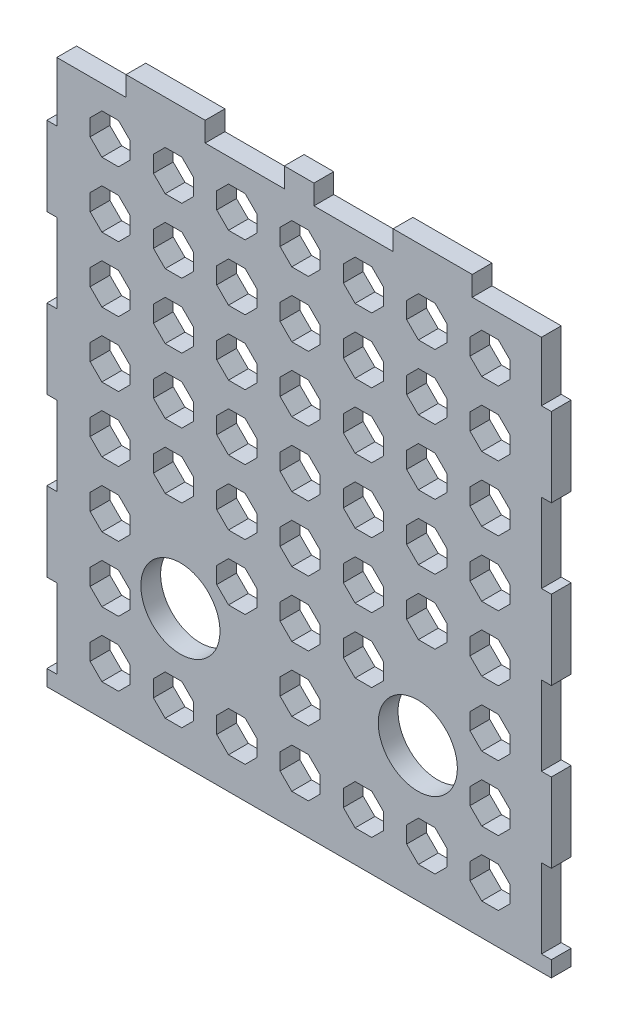
SolidWorks part; units mm, degrees
material "Oak"
ref_plane "Front Plane" through (0, 0, 0) normal (0, 0, 1) x (1, 0, 0)
ref_plane "Top Plane" through (0, 0, 0) normal (0, 1, 0) x (1, 0, 0)
ref_plane "Right Plane" through (0, 0, 0) normal (1, 0, 0) x (0, 0, -1)
sketch "Sketch1" plane through (0, 0, 0) normal (0, 0, 1) x (1, 0, 0)
  line L1 (0, 0) -> (80.9625, 0)
  line L2 (0, 0) -> (0, -91.44)
  line L3 (0, -91.44) -> (80.9625, -91.44)
  line L4 (80.9625, 0) -> (80.9625, -91.44)
extrude "Boss-Extrude1" add sketch "Sketch1" along normal blind 3.175
sketch "Sketch2" plane through (0, 0, 3.175) normal (0, 0, 1) x (1, 0, 0)
  line L0 (0, 0) -> (1.5875, 0)
  line L1 (80.9625, 0) -> (0, 0) construction
  line L2 (1.5875, 0) -> (1.5875, -12.7)
  line L3 (1.5875, -12.7) -> (0, -12.7)
  line L4 (0, 0) -> (0, -91.44) construction
  line L5 (0, -12.7) -> (0, 0)
extrude "Cut-Extrude1" cut sketch "Sketch2" against normal through all
pattern_linear "LPattern1" count 5 spacing 25.4 along (0, -1, 0) of "Cut-Extrude1"
sketch "Sketch5" plane through (0, 0, 3.175) normal (0, 0, 1) x (1, 0, 0)
  line L1 (0, 0) -> (12.7, 0)
  line L2 (0, 0) -> (0, -3.175)
  line L3 (0, -3.175) -> (12.7, -3.175)
  line L4 (12.7, 0) -> (12.7, -3.175)
extrude "Cut-Extrude2" cut sketch "Sketch5" against normal through all
pattern_linear "LPattern2" count 2 spacing 25.4 along (1, 0, 0) of "Cut-Extrude2"
ref_plane "Plane1" through (40.4812, 0, 0) normal (1, 0, 0) x (0, 0, -1)
hole_wizard "Hole1" positions "Sketch7" profile "Sketch6" legacy
sketch "Sketch7" plane through (0, 0, 3.175) normal (0, 0, 1) x (1, 0, 0)
  line L0 (40.4812, -1.7463) -> (40.4812, 1.7463) construction
  line L1 (25.4, 0) -> (12.7, 0) construction
  point P0 (21.4312, -69.85)
  point P11 (19.05, 0)
  dimension "D1" = 19.05
  dimension "D2" = 69.85
sketch "Sketch6" plane through (21.4312, -69.85, 3.175) normal (1, 0, 0) x (0, -1, 0)
  line L0 (0, 0) -> (0, 93.98)
  line L1 (0, 93.98) -> (6.35, 93.98)
  line L2 (6.35, 93.98) -> (6.35, 0)
  line L3 (6.35, 0) -> (0, 0)
  line L4 (0, 110) -> (0, -10) construction
  dimension "Diameter" = 12.7
  dimension "Depth" = 93.98
mirror "Mirror1" about plane through (40.4812, 0, 0) normal (1, 0, 0) of "Hole1", "Cut-Extrude1", "LPattern1", "Cut-Extrude2", "LPattern2"
hole_wizard "Hole2" [suppressed] positions "Sketch9" profile "Sketch8" legacy
sketch "Sketch9" plane through (0, 0, 2.54) normal (0, 0, 1) x (1, 0, 0)
  point P0 (10.16, -10.16)
sketch "Sketch8" plane through (10.16, -10.16, 2.54) normal (1, 0, 0) x (0, -1, 0)
  line L0 (0, 0) -> (0, 2.54)
  line L1 (0, 2.54) -> (3.175, 2.54)
  line L2 (3.175, 2.54) -> (3.175, 0)
  line L3 (3.175, 0) -> (0, 0)
  line L4 (0, 110) -> (0, -10) construction
  dimension "Diameter" = 6.35
  dimension "Depth" = 2.54
pattern_linear "LPattern5" [suppressed] count 8 spacing 10.16 count 7 spacing 10.1071
sketch "Sketch10" plane through (0, 0, 3.175) normal (0, 0, 1) x (1, 0, 0)
  line L1 (13.3794, -8.8709) -> (11.4935, -6.985)
  line L2 (11.4935, -6.985) -> (8.8265, -6.985)
  line L3 (8.8265, -6.985) -> (6.9406, -8.8709)
  line L4 (6.9406, -8.8709) -> (6.9406, -11.5379)
  line L5 (6.9406, -11.5379) -> (8.8265, -13.4237)
  line L6 (8.8265, -13.4237) -> (11.4935, -13.4237)
  line L7 (11.4935, -13.4237) -> (13.3794, -11.5379)
  line L8 (13.3794, -11.5379) -> (13.3794, -8.8709)
  circle A0 centre (10.16, -10.2044) radius 3.2194 construction
extrude "Cut-Extrude3" cut sketch "Sketch10" against normal through all
pattern_linear "LPattern6" count 7 spacing 10.16 along (1, 0, 0) count 8 spacing 10.414 along (0, -1, 0) skipping (1, 5), (1, 6), (2, 6), (4, 6), (5, 5), (5, 6) of "Cut-Extrude3"
